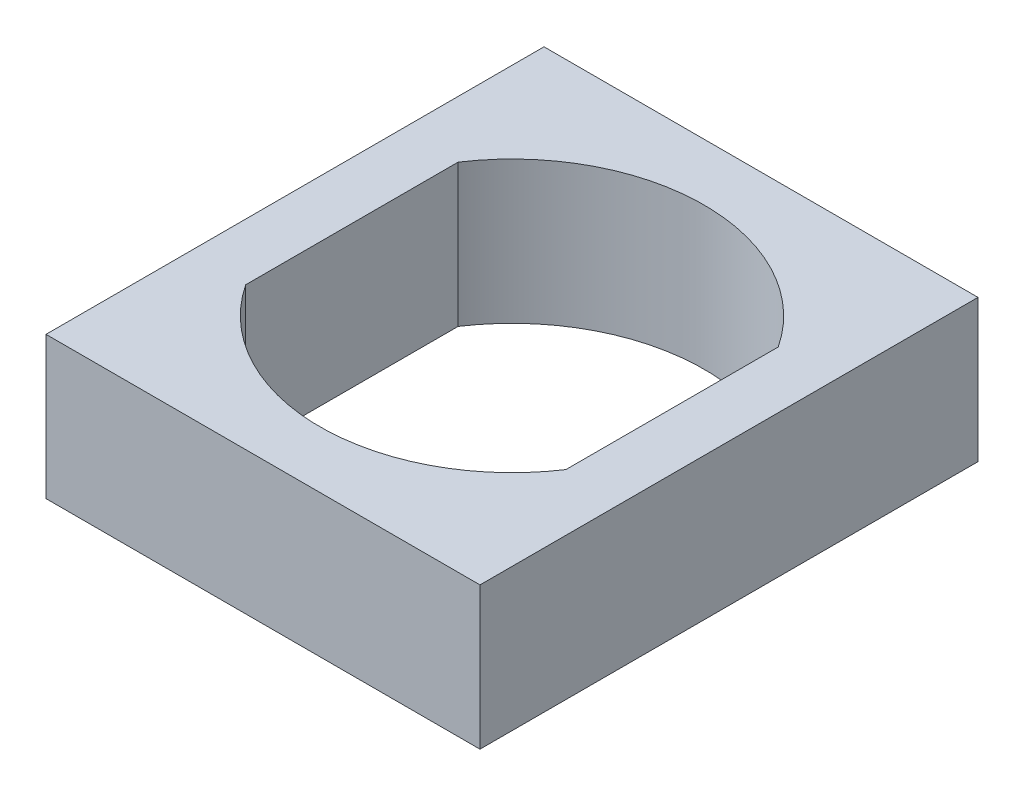
SolidWorks part; units mm, degrees
ref_plane "Front Plane" through (0, 0, 0) normal (0, 0, 1) x (1, 0, 0)
ref_plane "Top Plane" through (0, 0, 0) normal (0, 1, 0) x (1, 0, 0)
ref_plane "Right Plane" through (0, 0, 0) normal (1, 0, 0) x (0, 0, -1)
sketch "Sketch1" plane through (0, 45.5089, 0) normal (0, 1, 0) x (1, 0, 0)
  line L0 (28.9803, -65.4258) -> (32.2528, -65.4258) construction
  line L1 (27.3666, -72.8258) -> (33.8666, -72.8258) construction
  line L2 (27.3666, -72.8258) -> (27.3666, -65.4258) construction
  line L3 (27.3666, -65.4258) -> (33.8666, -65.4258) construction
  line L4 (33.8666, -72.8258) -> (33.8666, -65.4258) construction
  line L5 (28.9803, -72.8258) -> (32.2528, -72.8258) construction
  line L6 (27.3666, -71.5517) -> (27.3666, -66.7) construction
  line L7 (33.8666, -71.5517) -> (33.8666, -66.7) construction
  line L8 (27.5666, -72.6258) -> (33.6666, -72.6258)
  line L9 (33.6666, -72.6258) -> (33.6666, -65.6258)
  line L10 (27.5666, -65.6258) -> (33.6666, -65.6258)
  line L11 (27.5666, -72.6258) -> (27.5666, -65.6258)
  line L12 (28.5166, -67.6793) -> (28.5166, -70.5724) construction
  line L13 (32.7166, -67.6793) -> (32.7166, -70.5724) construction
  line L14 (28.5166, -69.1258) -> (30.6166, -69.1258) construction
  line L15 (30.6166, -69.1258) -> (32.7166, -69.1258) construction
  line L16 (32.8666, -67.6334) -> (32.8666, -70.6183)
  line L17 (28.3666, -67.6334) -> (28.3666, -70.6183)
  arc A0 (32.7166, -67.6793) -> (28.5166, -67.6793) centre (30.6166, -69.1258) ccw construction
  arc A1 (28.5166, -70.5724) -> (32.7166, -70.5724) centre (30.6166, -69.1258) ccw construction
  arc A2 (28.3666, -70.6183) -> (32.8666, -70.6183) centre (30.6166, -69.1258) ccw
  arc A3 (32.8666, -67.6334) -> (28.3666, -67.6334) centre (30.6166, -69.1258) ccw
  point P19 (27.5666, -69.1258)
  point P20 (30.6166, -65.6258)
  dimension "D2" = 5.1
  dimension "D3" = 4.2
  dimension "D4" = 0.15
  dimension "D1" = 0.2
extrude "Boss-Extrude1" add sketch "Sketch1" along normal up to surface (2 mm away)
